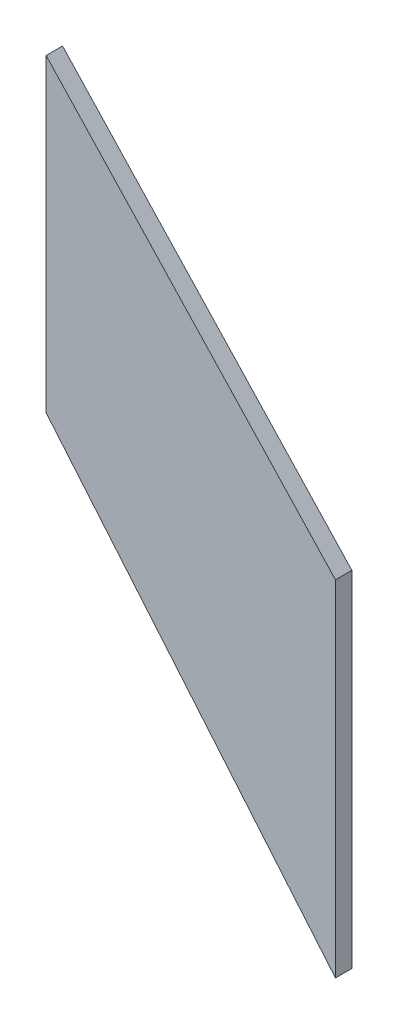
SolidWorks part; units mm, degrees
ref_plane "Front Plane" through (0, 0, 0) normal (0, 0, 1) x (1, 0, 0)
ref_plane "Top Plane" through (0, 0, 0) normal (0, 1, 0) x (1, 0, 0)
ref_plane "Right Plane" through (0, 0, 0) normal (1, 0, 0) x (0, 0, -1)
sketch "Sketch1" plane through (0, 0, 0) normal (0, 0, 1) x (1, 0, 0)
  line L0 (-101.2374, 0) -> (0, 0) construction
  line L1 (0, 0) -> (-101.2374, 120.65) construction
  line L2 (-101.2374, 120.65) -> (-101.2374, 0) construction
  line L3 (-101.2374, 120.65) -> (0, 0)
  line L4 (0, 0) -> (0, 120.65)
  line L5 (-101.2374, 120.65) -> (0, 120.65)
  line L7 (-101.2374, 120.65) -> (0, 120.65)
  line L8 (-101.2374, 120.65) -> (-101.2374, 216.5435)
  line L9 (-101.2374, 216.5435) -> (0, 216.5435)
  line L10 (0, 120.65) -> (0, 216.5435)
  dimension "D1" = 50
  dimension "D2" = 120.65
  dimension "D3" = 95.8935
extrude "Boss-Extrude1" add sketch "Sketch1" along normal blind 5.08 contours L5 L10 L9 L8 | L7 L3 L4
sketch "Sketch2" plane through (0, 0, 5.08) normal (0, 0, 1) x (1, 0, 0)
  line L0 (-101.2374, 216.5435) -> (0, 108.2717)
  line L1 (0, 0) -> (0, 216.5435) construction
  line L2 (0, 108.2717) -> (0, 216.5435)
  line L3 (0, 216.5435) -> (-101.2374, 216.5435)
extrude "Cut-Extrude1" cut sketch "Sketch2" against normal blind 50.8
sketch "Sketch3" plane through (0, 0, 5.08) normal (0, 0, 1) x (1, 0, 0)
  line L1 (-11.5788, 133.1882) -> (22.7991, 133.1882)
  line L2 (-11.5788, 133.1882) -> (-11.5788, -8.4019)
  line L3 (-11.5788, -8.4019) -> (22.7991, -8.4019)
  line L4 (22.7991, 133.1882) -> (22.7991, -8.4019)
extrude "Cut-Extrude2" cut sketch "Sketch3" against normal blind 25.4
sketch "Sketch4" plane through (0, 0, 0) normal (-0.766, -0.6428, 0) x (0, 0, 1)
  line L0 (2.54, 157.4974) -> (2.54, 18.0134) construction
  line L1 (5.08, 157.4974) -> (0, 157.4974) construction
  line L2 (0, 18.0134) -> (5.08, 18.0134) construction
  circle A0 centre (2.54, 26.4129) radius 1.4224
  circle A1 centre (2.54, 153.4129) radius 1.4224
  point P10 (2.54, 24.3288)
  point P11 (2.54, 153.4129)
  dimension "D1" = 127
extrude "Cut-Extrude3" cut sketch "Sketch4" against normal blind 5.08
